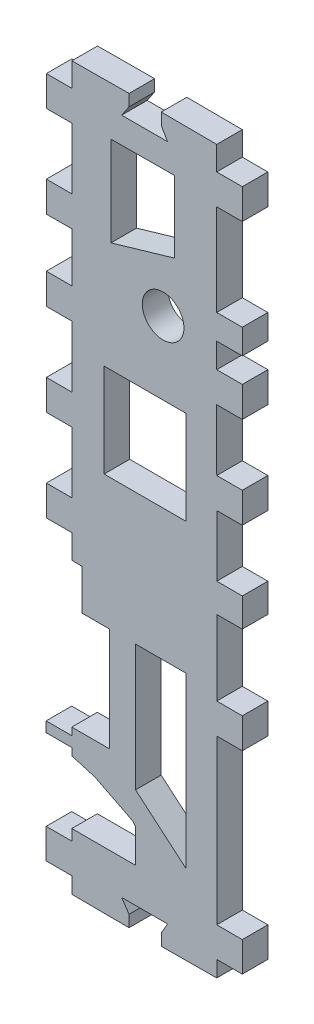
SolidWorks part; units mm, degrees
ref_plane "前视基准面" through (0, 0, 0) normal (0, 0, 1) x (1, 0, 0)
ref_plane "上视基准面" through (0, 0, 0) normal (0, 1, 0) x (1, 0, 0)
ref_plane "右视基准面" through (0, 0, 0) normal (1, 0, 0) x (0, 0, -1)
sketch "草图2" plane through (0, 0, 0) normal (0, 0, 1) x (1, 0, 0)
  line L0 (-135.1352, 3.2613) -> (-131.1829, 3.1397)
  line L130 (-135.1777, -109.9106) -> (-135.1777, -103.6168)
  line L131 (-135.1777, -103.6168) -> (-145.2016, -103.6168)
  line L132 (-145.2016, -103.6168) -> (-145.2016, -91.9008)
  line L133 (-145.2016, -91.9008) -> (-135.1777, -91.9008)
  line L134 (-68.4966, -16.1249) -> (-78.483, -16.1249)
  line L135 (-68.4966, -27.9763) -> (-68.4966, -16.1249)
  line L136 (-78.483, -27.9763) -> (-68.4966, -27.9763)
  line L137 (-78.483, -91.9008) -> (-78.483, -27.9763)
  line L138 (-68.4966, -91.9008) -> (-78.483, -91.9008)
  line L139 (-68.4966, -103.6168) -> (-68.4966, -91.9008)
  line L140 (-78.483, -103.6168) -> (-68.4966, -103.6168)
  line L141 (-78.483, -109.9106) -> (-78.483, -103.6168)
  line L142 (-100.1819, -110.0322) -> (-100.1819, -105.488)
  line L143 (-97.7198, -101.2184) -> (-100.1819, -105.488)
  line L144 (-115.6791, -101.2184) -> (-97.7198, -101.2184)
  line L145 (-112.7825, -105.488) -> (-115.6791, -101.2184)
  line L146 (-112.7825, -105.488) -> (-112.7825, -110.0322)
  line L147 (-112.7825, -110.0322) -> (-135.1777, -109.9106)
  line L148 (-100.1819, -110.0322) -> (-78.483, -109.9106)
  line L151 (-110.188, -74.5391) -> (-111.2598, -73.1994)
  line L152 (-126.064, -65.6968) -> (-111.2598, -73.1994)
  line L153 (-135.1777, -63.0175) -> (-126.064, -65.6968)
  line L154 (-135.1777, -60.1952) -> (-135.1777, -63.0175)
  line L155 (-78.483, -16.1249) -> (-78.483, 3.0902)
  line L157 (-135.1777, -53.2765) -> (-120.5124, -53.2765)
  line L158 (-135.1777, -56.1776) -> (-145.2016, -56.1775)
  line L159 (-135.1777, -56.1776) -> (-135.1777, -53.2765)
  line L165 (-131.1829, -12.6913) -> (-131.1829, 3.1397)
  line L166 (-120.5124, -12.6913) -> (-131.1829, -12.6913)
  line L167 (-135.1777, -87.6306) -> (-110.188, -87.6306)
  line L168 (-135.1777, -87.6306) -> (-135.1777, -91.9008)
  line L169 (-145.2016, -60.1952) -> (-145.2016, -56.1775)
  line L170 (-145.2016, -60.1952) -> (-135.1777, -60.1952)
  line L171 (-110.2308, -12.6913) -> (-90.5937, -12.6913)
  line L172 (-110.2308, -12.6913) -> (-110.2308, -62.066)
  line L173 (-120.5124, -12.6913) -> (-120.5124, -53.2765)
  line L174 (-90.5937, -78.7769) -> (-110.2308, -62.066)
  line L175 (-135.1352, 3.2613) -> (-135.1352, 12.5879)
  line L176 (-135.1352, 12.5879) -> (-145.1216, 12.5879)
  line L177 (-145.1216, 12.5879) -> (-145.1216, 24.3965)
  line L178 (-145.1216, 24.3965) -> (-135.1352, 24.3965)
  line L179 (-135.1352, 24.3965) -> (-135.1352, 48.3424)
  line L180 (-135.1352, 48.3424) -> (-145.1216, 48.3424)
  line L181 (-145.1216, 48.3424) -> (-145.1216, 60.1758)
  line L182 (-145.1216, 60.1758) -> (-135.1352, 60.1758)
  line L183 (-68.4966, 60.2637) -> (-78.483, 60.2637)
  line L184 (-68.4966, 48.4122) -> (-68.4966, 60.2637)
  line L185 (-78.483, 48.4122) -> (-68.4966, 48.4122)
  line L186 (-78.483, 24.4709) -> (-78.483, 48.4122)
  line L187 (-68.4966, 24.4709) -> (-78.483, 24.4709)
  line L188 (-68.4965, 13.2206) -> (-68.4966, 24.4709)
  line L189 (-78.4829, 13.2206) -> (-68.4965, 13.2206)
  line L190 (-78.4829, 3.2613) -> (-78.4829, 13.2206)
  line L193 (-90.5937, 38.7391) -> (-122.5208, 38.848)
  line L194 (-78.483, 60.2637) -> (-78.483, 63.9654)
  line L196 (-135.1352, 63.9538) -> (-135.1352, 60.1758)
  line L198 (-119.8632, 118.3618) -> (-119.8632, 153.5138)
  line L199 (-105.2152, 109.5498) -> (-106.9792, 106.9098)
  line L200 (-102.5752, 111.3138) -> (-99.4632, 111.9338)
  line L201 (-107.5992, 103.7978) -> (-106.9792, 100.6818)
  line L202 (-102.5752, 111.3138) -> (-105.2152, 109.5498)
  line L203 (-106.9792, 100.6818) -> (-105.2152, 98.0418)
  line L204 (-106.9792, 106.9098) -> (-107.5992, 103.7978)
  line L205 (-105.2152, 98.0418) -> (-102.5752, 96.2778)
  line L206 (-119.8632, 118.3618) -> (-94.9432, 125.6458)
  line L207 (-91.9432, 100.6818) -> (-93.7072, 98.0418)
  line L208 (-96.3472, 96.2778) -> (-93.7072, 98.0418)
  line L209 (-91.9432, 100.6818) -> (-91.3272, 103.7978)
  line L210 (-91.9432, 106.9098) -> (-93.7072, 109.5498)
  line L211 (-96.3472, 111.3138) -> (-93.7072, 109.5498)
  line L212 (-99.4632, 95.6618) -> (-102.5752, 96.2778)
  line L213 (-96.3472, 111.3138) -> (-99.4632, 111.9338)
  line L214 (-91.9432, 106.9098) -> (-91.3272, 103.7978)
  line L215 (-96.3472, 96.2778) -> (-99.4632, 95.6618)
  line L216 (-145.1232, 163.0738) -> (-145.1232, 151.2658)
  line L217 (-135.1352, 151.2658) -> (-145.1232, 151.2658)
  line L218 (-135.1352, 163.0738) -> (-135.1352, 172.4018)
  line L219 (-135.1352, 127.3218) -> (-135.1352, 151.2658)
  line L220 (-135.1352, 127.3218) -> (-145.1232, 127.3218)
  line L221 (-135.1352, 163.0738) -> (-145.1232, 163.0738)
  line L222 (-145.1232, 127.3218) -> (-145.1232, 115.4858)
  line L223 (-145.1232, 115.4858) -> (-135.1352, 115.4858)
  line L224 (-122.5352, 75.3178) -> (-90.5792, 75.3178)
  line L225 (-135.1352, 115.4858) -> (-135.1352, 96.1498)
  line L226 (-145.1232, 96.1498) -> (-135.1352, 96.1498)
  line L227 (-122.5208, 63.9538) -> (-122.5352, 68.0098)
  line L228 (-90.5792, 75.3178) -> (-90.5792, 68.0098)
  line L229 (-135.1352, 84.2298) -> (-145.1232, 84.2298)
  line L230 (-90.5792, 68.0098) -> (-90.5937, 63.9654)
  line L231 (-135.1352, 84.2298) -> (-135.1352, 63.9538)
  line L232 (-145.1232, 84.2298) -> (-145.1232, 96.1498)
  line L233 (-122.5352, 68.0098) -> (-122.5352, 75.3178)
  line L234 (-78.4952, 115.4738) -> (-78.4952, 151.2658)
  line L235 (-78.4952, 96.1098) -> (-78.4952, 105.7618)
  line L236 (-68.4992, 151.2658) -> (-78.4952, 151.2658)
  line L237 (-78.4952, 84.2378) -> (-68.4992, 84.2378)
  line L238 (-68.4992, 84.2378) -> (-68.4992, 96.1098)
  line L239 (-68.4992, 115.4738) -> (-68.4992, 105.7618)
  line L240 (-78.4952, 115.4738) -> (-68.4992, 115.4738)
  line L241 (-68.4992, 105.7618) -> (-78.4952, 105.7618)
  line L242 (-78.4952, 96.1098) -> (-68.4992, 96.1098)
  line L243 (-115.6792, 163.7098) -> (-97.7232, 163.7098)
  line L244 (-112.7832, 172.5218) -> (-135.1352, 172.4018)
  line L245 (-78.4952, 172.4018) -> (-78.4952, 163.0738)
  line L246 (-68.4992, 163.0738) -> (-78.4952, 163.0738)
  line L247 (-68.4992, 163.0738) -> (-68.4992, 151.2658)
  line L248 (-112.7832, 167.9778) -> (-112.7832, 172.5218)
  line L249 (-78.483, 63.9654) -> (-78.4952, 84.2378)
  line L250 (-100.1832, 172.5218) -> (-100.1832, 167.9778)
  line L251 (-115.6792, 163.7098) -> (-112.7832, 167.9778)
  line L252 (-97.7232, 163.7098) -> (-100.1832, 167.9778)
  line L253 (-100.1832, 172.5218) -> (-78.4952, 172.4018)
  line L254 (-94.9432, 153.6218) -> (-119.8632, 153.5138)
  line L255 (-90.5937, -78.7769) -> (-90.5937, -12.6913)
  line L256 (-110.188, -87.6306) -> (-110.188, -74.5391)
  line L257 (-122.5208, 38.848) -> (-122.5208, 63.9538)
  line L258 (-90.5937, 38.7391) -> (-90.5937, 63.9654)
  line L259 (-94.9432, 125.6458) -> (-94.9432, 153.6218)
sketch "草图4" plane through (0, 0, 0) normal (0, 0, 1) x (1, 0, 0)
  line L0 (-115.6792, 163.7098) -> (-112.7832, 167.9778)
  line L1 (-112.7832, 167.9778) -> (-112.7832, 172.5218)
  line L2 (-112.7832, 172.5218) -> (-135.1352, 172.4018)
  line L3 (-135.1352, 172.4018) -> (-135.1352, 163.0738)
  line L4 (-135.1352, 163.0738) -> (-145.1232, 163.0738)
  line L5 (-145.1232, 163.0738) -> (-145.1232, 151.2658)
  line L6 (-145.1232, 151.2658) -> (-135.1352, 151.2658)
  line L7 (-135.1352, 151.2658) -> (-135.1352, 127.3218)
  line L8 (-135.1352, 127.3218) -> (-145.1232, 127.3218)
  line L9 (-145.1232, 127.3218) -> (-145.1232, 115.4858)
  line L10 (-145.1232, 115.4858) -> (-135.1352, 115.4858)
  line L11 (-135.1352, 115.4858) -> (-135.1352, 96.1498)
  line L12 (-135.1352, 96.1498) -> (-145.1232, 96.1498)
  line L13 (-145.1232, 96.1498) -> (-145.1232, 84.2298)
  line L14 (-145.1232, 84.2298) -> (-135.1352, 84.2298)
  line L15 (-135.1352, 84.2298) -> (-135.1352, 60.1758)
  line L16 (-135.1352, 60.1758) -> (-145.1216, 60.1758)
  line L17 (-145.1216, 60.1758) -> (-145.1216, 48.3424)
  line L18 (-145.1216, 48.3424) -> (-135.1352, 48.3424)
  line L19 (-135.1352, 48.3424) -> (-135.1352, 24.3965)
  line L20 (-135.1352, 24.3965) -> (-145.1216, 24.3965)
  line L21 (-145.1216, 24.3965) -> (-145.1216, 12.5879)
  line L22 (-145.1216, 12.5879) -> (-135.1352, 12.5879)
  line L23 (-135.1352, 12.5879) -> (-135.1352, 3.2613)
  line L24 (-135.1352, 3.2613) -> (-131.1829, 3.1397)
  line L25 (-131.1829, 3.1397) -> (-131.1829, -12.6913)
  line L26 (-131.1829, -12.6913) -> (-120.5124, -12.6913)
  line L27 (-120.5124, -12.6913) -> (-120.5124, -53.2765)
  line L28 (-120.5124, -53.2765) -> (-135.1777, -53.2765)
  line L29 (-135.1777, -53.2765) -> (-135.1777, -56.1776)
  line L30 (-135.1777, -56.1776) -> (-145.2016, -56.1775)
  line L31 (-145.2016, -56.1775) -> (-145.2016, -60.1952)
  line L32 (-145.2016, -60.1952) -> (-135.1777, -60.1952)
  line L33 (-135.1777, -60.1952) -> (-135.1777, -63.0175)
  line L34 (-135.1777, -63.0175) -> (-126.064, -65.6968)
  line L35 (-126.064, -65.6968) -> (-111.2598, -73.1994)
  line L36 (-111.2598, -73.1994) -> (-110.188, -74.5391)
  line L37 (-110.188, -74.5391) -> (-110.188, -87.6306)
  line L38 (-110.188, -87.6306) -> (-135.1777, -87.6306)
  line L39 (-135.1777, -87.6306) -> (-135.1777, -91.9008)
  line L40 (-135.1777, -91.9008) -> (-145.2016, -91.9008)
  line L41 (-145.2016, -91.9008) -> (-145.2016, -103.6168)
  line L42 (-145.2016, -103.6168) -> (-135.1777, -103.6168)
  line L43 (-135.1777, -103.6168) -> (-135.1777, -109.9106)
  line L44 (-135.1777, -109.9106) -> (-112.7825, -110.0322)
  line L45 (-112.7825, -110.0322) -> (-112.7825, -105.488)
  line L46 (-112.7825, -105.488) -> (-115.6791, -101.2184)
  line L47 (-115.6791, -101.2184) -> (-97.7198, -101.2184)
  line L48 (-97.7198, -101.2184) -> (-100.1819, -105.488)
  line L49 (-100.1819, -105.488) -> (-100.1819, -110.0322)
  line L50 (-100.1819, -110.0322) -> (-78.483, -109.9106)
  line L51 (-78.483, -109.9106) -> (-78.483, -103.6168)
  line L52 (-78.483, -103.6168) -> (-68.4966, -103.6168)
  line L53 (-68.4966, -103.6168) -> (-68.4966, -91.9008)
  line L54 (-68.4966, -91.9008) -> (-78.483, -91.9008)
  line L55 (-78.483, -91.9008) -> (-78.483, -27.9763)
  line L56 (-78.483, -27.9763) -> (-68.4966, -27.9763)
  line L57 (-68.4966, -27.9763) -> (-68.4966, -16.1249)
  line L58 (-68.4966, -16.1249) -> (-78.483, -16.1249)
  line L59 (-78.483, -16.1249) -> (-78.4829, 13.2206)
  line L60 (-78.4829, 13.2206) -> (-68.4965, 13.2206)
  line L61 (-68.4965, 13.2206) -> (-68.4966, 24.4709)
  line L62 (-68.4966, 24.4709) -> (-78.483, 24.4709)
  line L63 (-78.483, 24.4709) -> (-78.483, 48.4122)
  line L64 (-78.483, 48.4122) -> (-68.4966, 48.4122)
  line L65 (-68.4966, 48.4122) -> (-68.4966, 60.2637)
  line L66 (-68.4966, 60.2637) -> (-78.483, 60.2637)
  line L67 (-78.483, 60.2637) -> (-78.4952, 84.2378)
  line L68 (-78.4952, 84.2378) -> (-68.4992, 84.2378)
  line L69 (-68.4992, 84.2378) -> (-68.4992, 96.1098)
  line L70 (-68.4992, 96.1098) -> (-78.4952, 96.1098)
  line L71 (-78.4952, 96.1098) -> (-78.4952, 105.7618)
  line L72 (-78.4952, 105.7618) -> (-68.4992, 105.7618)
  line L73 (-68.4992, 105.7618) -> (-68.4992, 115.4738)
  line L74 (-68.4992, 115.4738) -> (-78.4952, 115.4738)
  line L75 (-78.4952, 115.4738) -> (-78.4952, 151.2658)
  line L76 (-78.4952, 151.2658) -> (-68.4992, 151.2658)
  line L77 (-68.4992, 151.2658) -> (-68.4992, 163.0738)
  line L78 (-68.4992, 163.0738) -> (-78.4952, 163.0738)
  line L79 (-78.4952, 163.0738) -> (-78.4952, 172.4018)
  line L80 (-78.4952, 172.4018) -> (-100.1832, 172.5218)
  line L81 (-100.1832, 172.5218) -> (-100.1832, 167.9778)
  line L82 (-100.1832, 167.9778) -> (-97.7232, 163.7098)
  line L83 (-97.7232, 163.7098) -> (-115.6792, 163.7098)
  line L84 (-110.2308, -12.6913) -> (-90.5937, -12.6913)
  line L85 (-122.5352, 75.3178) -> (-90.5937, 75.3178)
  line L86 (-122.5352, 75.3178) -> (-122.5352, 38.7391)
  line L87 (-122.5352, 38.7391) -> (-90.5937, 38.7391)
  line L88 (-90.5937, 75.3178) -> (-90.5937, 38.7391)
  line L89 (-90.5937, -12.6913) -> (-90.5937, -78.7769)
  line L90 (-110.2308, -12.6913) -> (-110.2308, -62.066)
  line L91 (-110.2308, -62.066) -> (-90.5937, -78.7769)
  line L92 (-119.8632, 153.5138) -> (-94.9432, 153.6218)
  line L93 (-94.9432, 153.6218) -> (-94.9432, 125.6458)
  line L94 (-94.9432, 125.6458) -> (-119.8632, 118.3618)
  line L95 (-119.8632, 118.3618) -> (-119.8632, 153.5138)
  circle A0 centre (-99.4615, 103.796) radius 8.1377
extrude "凸台-拉伸1" add sketch "草图4" along normal blind 10
